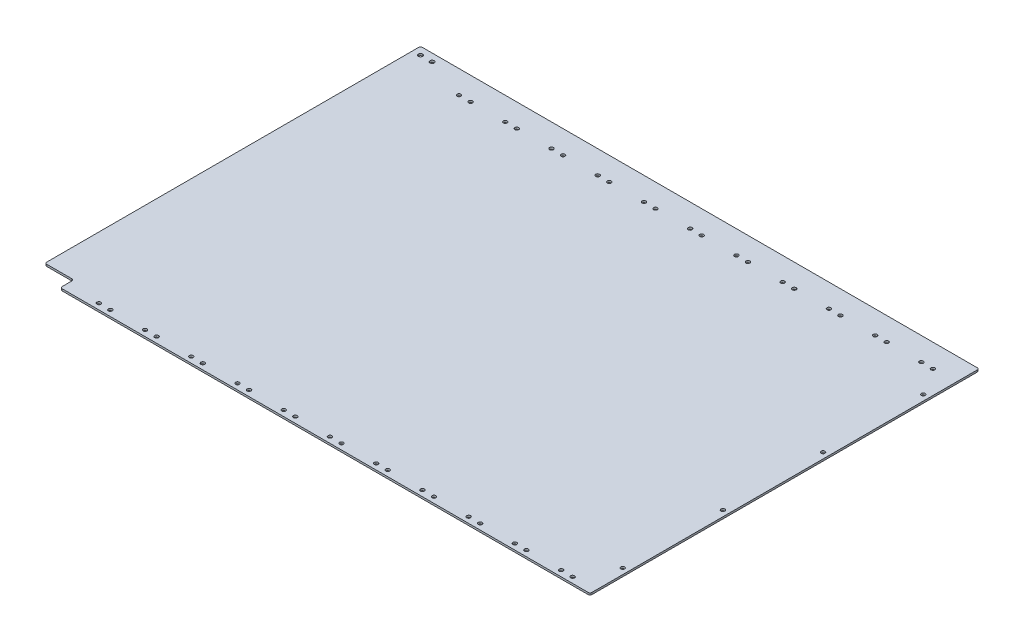
SolidWorks part; units mm, degrees
material "PC High Viscosity"
ref_plane "Front Plane" through (0, 0, 0) normal (0, 0, 1) x (1, 0, 0)
ref_plane "Top Plane" through (0, 0, 0) normal (0, 1, 0) x (1, 0, 0)
ref_plane "Right Plane" through (0, 0, 0) normal (1, 0, 0) x (0, 0, -1)
sketch "Sketch1" plane through (0, 0, 0) normal (0, 1, 0) x (1, 0, 0)
  line L1 (0, 0) -> (920.75, 0)
  line L2 (0, 0) -> (0, 641.35)
  line L3 (0, 641.35) -> (920.75, 641.35)
  line L4 (920.75, 0) -> (920.75, 641.35)
  dimension "D1" = 920.75
  dimension "D2" = 641.35
extrude "Boss-Extrude1" add sketch "Sketch1" along normal blind 3.175
sketch "Sketch2" plane through (0, 3.175, 0) normal (0, 1, 0) x (1, 0, 0)
  line L0 (0, 641.35) -> (0, 0) construction
  line L5 (0, 0) -> (47.625, 0)
  line L6 (0, 0) -> (0, 22.225)
  line L7 (0, 22.225) -> (47.625, 22.225)
  line L8 (47.625, 0) -> (47.625, 22.225)
  line L9 (920.75, 641.35) -> (0, 641.35) construction
  line L10 (0, 0) -> (920.75, 0) construction
  line L11 (920.75, 0) -> (920.75, 641.35) construction
  circle A0 centre (12.7, 628.65) radius 3.429
  circle A1 centre (31.75, 628.65) radius 3.429
  circle A2 centre (101.6, 9.525) radius 3.175
  circle A3 centre (120.65, 9.525) radius 3.175
  circle A4 centre (196.85, 9.525) radius 3.175
  circle A5 centre (177.8, 9.525) radius 3.175
  circle A6 centre (273.05, 9.525) radius 3.175
  circle A7 centre (254, 9.525) radius 3.175
  circle A8 centre (349.25, 9.525) radius 3.175
  circle A9 centre (330.2, 9.525) radius 3.175
  circle A10 centre (425.45, 9.525) radius 3.175
  circle A11 centre (406.4, 9.525) radius 3.175
  circle A12 centre (501.65, 9.525) radius 3.175
  circle A13 centre (482.6, 9.525) radius 3.175
  circle A14 centre (577.85, 9.525) radius 3.175
  circle A15 centre (558.8, 9.525) radius 3.175
  circle A16 centre (654.05, 9.525) radius 3.175
  circle A17 centre (635, 9.525) radius 3.175
  circle A18 centre (730.25, 9.525) radius 3.175
  circle A19 centre (711.2, 9.525) radius 3.175
  circle A20 centre (806.45, 9.525) radius 3.175
  circle A21 centre (787.4, 9.525) radius 3.175
  circle A22 centre (882.65, 9.525) radius 3.175
  circle A23 centre (863.6, 9.525) radius 3.175
  circle A24 centre (882.65, 603.25) radius 3.175
  circle A25 centre (863.6, 603.25) radius 3.175
  circle A26 centre (806.45, 603.25) radius 3.175
  circle A27 centre (787.4, 603.25) radius 3.175
  circle A28 centre (730.25, 603.25) radius 3.175
  circle A29 centre (711.2, 603.25) radius 3.175
  circle A30 centre (635, 603.25) radius 3.175
  circle A31 centre (654.05, 603.25) radius 3.175
  circle A32 centre (482.6, 603.25) radius 3.175
  circle A33 centre (501.65, 603.25) radius 3.175
  circle A34 centre (558.8, 603.25) radius 3.175
  circle A35 centre (577.85, 603.25) radius 3.175
  circle A36 centre (425.45, 603.25) radius 3.175
  circle A37 centre (406.4, 603.25) radius 3.175
  circle A38 centre (120.65, 603.25) radius 3.175
  circle A39 centre (177.8, 603.25) radius 3.175
  circle A40 centre (196.85, 603.25) radius 3.175
  circle A41 centre (254, 603.25) radius 3.175
  circle A42 centre (273.05, 603.25) radius 3.175
  circle A43 centre (330.2, 603.25) radius 3.175
  circle A44 centre (349.25, 603.25) radius 3.175
  circle A45 centre (101.6, 603.25) radius 3.175
  circle A46 centre (911.225, 63.5) radius 3.175
  circle A47 centre (911.225, 228.6) radius 3.175
  circle A48 centre (911.225, 393.7) radius 3.175
  circle A49 centre (911.225, 558.8) radius 3.175
  dimension "D5" = 6.858
  dimension "D6" = 6.858
  dimension "D9" = 6.35
  dimension "D10" = 6.35
  dimension "D18" = 6.35
  dimension "D19" = 63.5
  dimension "D1" = 47.625
  dimension "D2" = 22.225
  dimension "D3" = 19.05
  dimension "D4" = 12.7
  dimension "D7" = 12.7
  dimension "D8" = 12.7
  dimension "D11" = 19.05
  dimension "D12" = 9.525
  dimension "D13" = 101.6
  dimension "D16" = 38.1
  dimension "D17" = 9.525
  dimension "D21" = 165.1
  dimension "D22" = 19.05
  dimension "D14" = 11
  dimension "D15" = 2
  dimension "D20" = 4
extrude "Cut-Extrude1" cut sketch "Sketch2" against normal blind 3.175
fillet "Fillet1" radius 3.175 6 edges at (0, 1.5875, -641.35) (920.75, 1.5875, -641.35) (920.75, 1.5875, 0) (47.625, 1.5875, 0) (47.625, 1.5875, -22.225) (0, 1.5875, -22.225)
